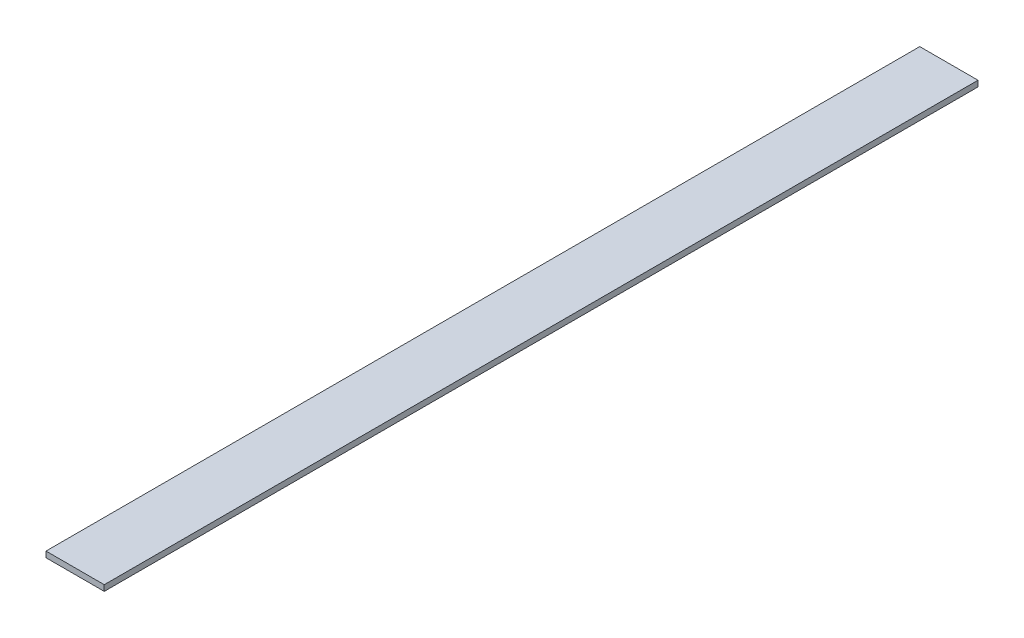
SolidWorks part; units mm, degrees
ref_plane "Front Plane" through (0, 0, 0) normal (0, 0, 1) x (1, 0, 0)
ref_plane "Top Plane" through (0, 0, 0) normal (0, 1, 0) x (1, 0, 0)
ref_plane "Right Plane" through (0, 0, 0) normal (1, 0, 0) x (0, 0, -1)
sketch "Sketch1" plane through (0, 0, 0) normal (0, 0, 1) x (1, 0, 0)
  line L1 (-29.8657, 4.3353) -> (-9.8657, 4.3353)
  line L2 (-29.8657, 4.3353) -> (-29.8657, 2.3353)
  line L3 (-29.8657, 2.3353) -> (-9.8657, 2.3353)
  line L4 (-9.8657, 4.3353) -> (-9.8657, 2.3353)
  line L5 (-29.8657, 4.3353) -> (-9.8657, 2.3353) construction
  line L6 (-29.8657, 2.3353) -> (-9.8657, 4.3353) construction
  point P0 (-19.8657, 3.3353)
extrude "Boss-Extrude1" add sketch "Sketch1" along normal blind 300
